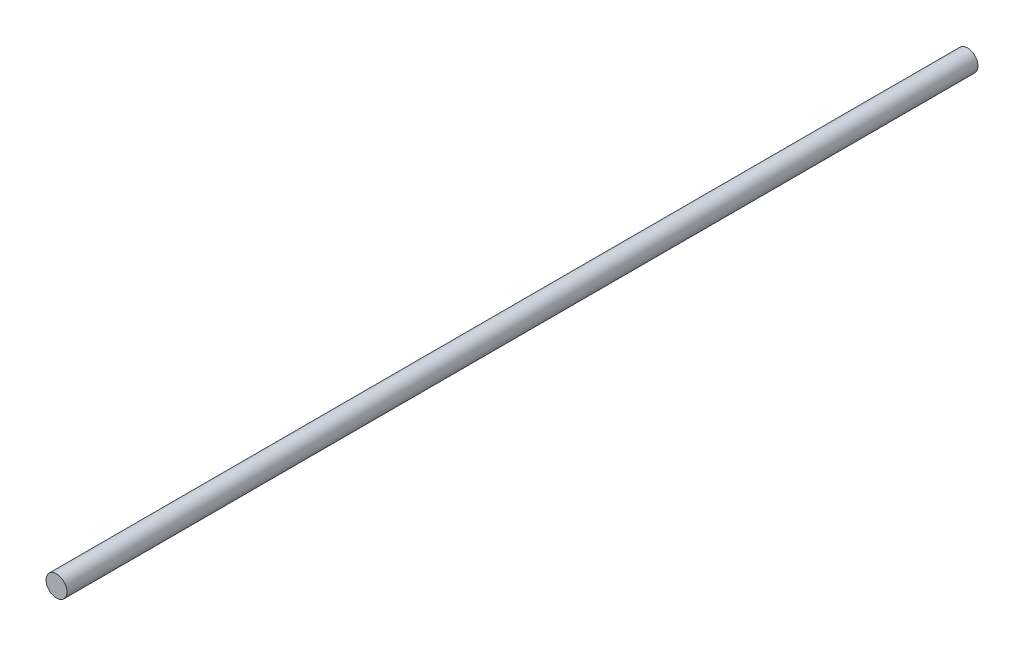
SolidWorks part; units mm, degrees
ref_plane "Płaszczyzna przednia" through (0, 0, 0) normal (0, 0, 1) x (1, 0, 0)
ref_plane "Płaszczyzna górna" through (0, 0, 0) normal (0, 1, 0) x (1, 0, 0)
ref_plane "Płaszczyzna prawa" through (0, 0, 0) normal (1, 0, 0) x (0, 0, -1)
sketch "Szkic1" plane through (0, 0, 0) normal (0, 0, 1) x (1, 0, 0)
  circle A0 centre (0, 0) radius 3
  dimension "D1" = 6
extrude "Dodanie-wyciągnięcie1" add sketch "Szkic1" along normal blind 260
